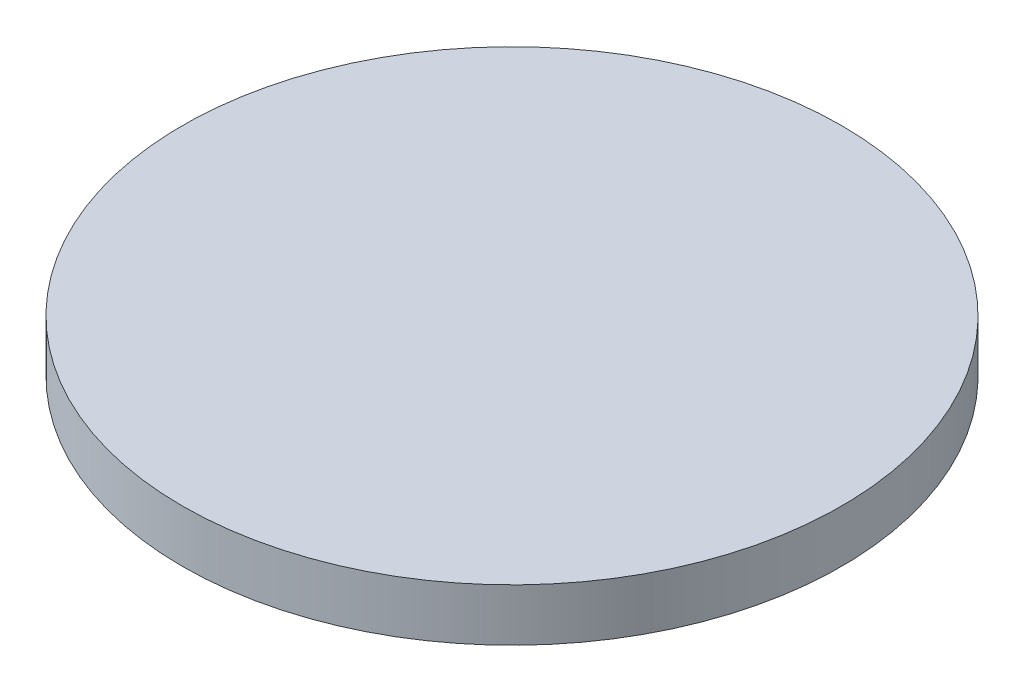
SolidWorks part; units mm, degrees
ref_plane "Front Plane" through (0, 0, 0) normal (0, 0, 1) x (1, 0, 0)
ref_plane "Top Plane" through (0, 0, 0) normal (0, 1, 0) x (1, 0, 0)
ref_plane "Right Plane" through (0, 0, 0) normal (1, 0, 0) x (0, 0, -1)
sketch "Sketch1" plane through (0, 0, 0) normal (0, 1, 0) x (1, 0, 0)
  circle A0 centre (0, 0) radius 40
  dimension "D1" = 80
extrude "Boss-Extrude1" add sketch "Sketch1" along normal blind 6.35
